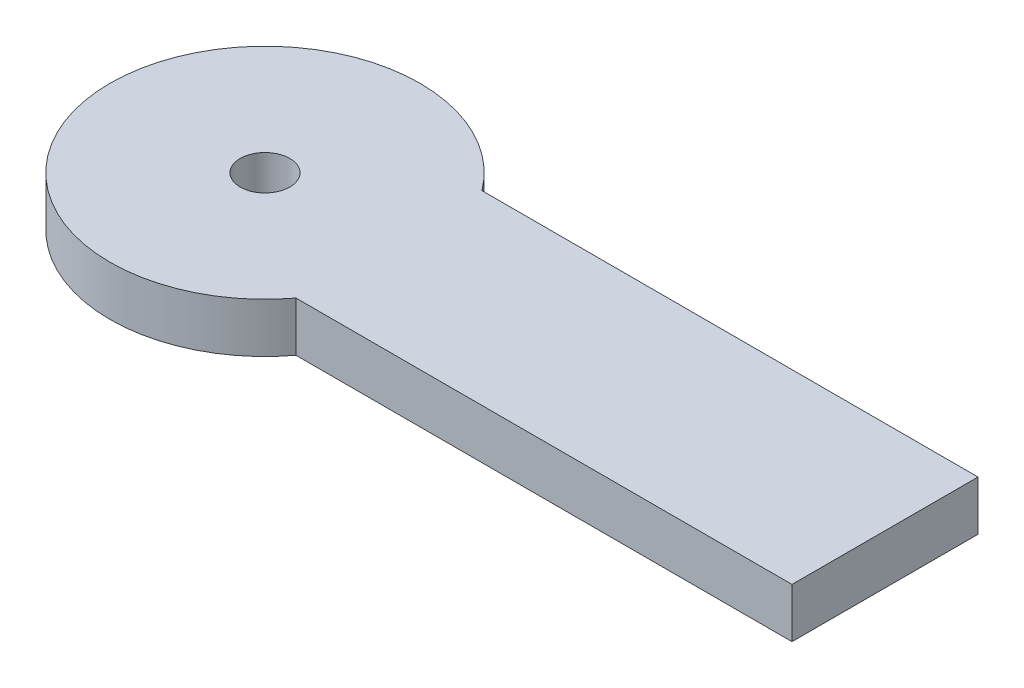
SolidWorks part; units mm, degrees
ref_plane "Front Plane" through (0, 0, 0) normal (0, 0, 1) x (1, 0, 0)
ref_plane "Top Plane" through (0, 0, 0) normal (0, 1, 0) x (1, 0, 0)
ref_plane "Right Plane" through (0, 0, 0) normal (1, 0, 0) x (0, 0, -1)
sketch "Sketch1" plane through (0, 0, 0) normal (0, 1, 0) x (1, 0, 0)
  line L0 (0, 0) -> (50, 0) construction
  line L1 (10, 7.5) -> (50, 7.5)
  line L2 (50, 7.5) -> (50, -7.5)
  line L3 (50, -7.5) -> (10, -7.5)
  arc A0 (10, 7.5) -> (10, -7.5) centre (0, 0) ccw
  circle A1 centre (0, 0) radius 2
  arc A2 (10, -7.5) -> (10, 7.5) centre (0, 0) ccw construction
  dimension "D1" = 4
  dimension "D2" = 25
  dimension "D3" = 15
  dimension "D4" = 50
extrude "Boss-Extrude1" add sketch "Sketch1" along normal blind 4
